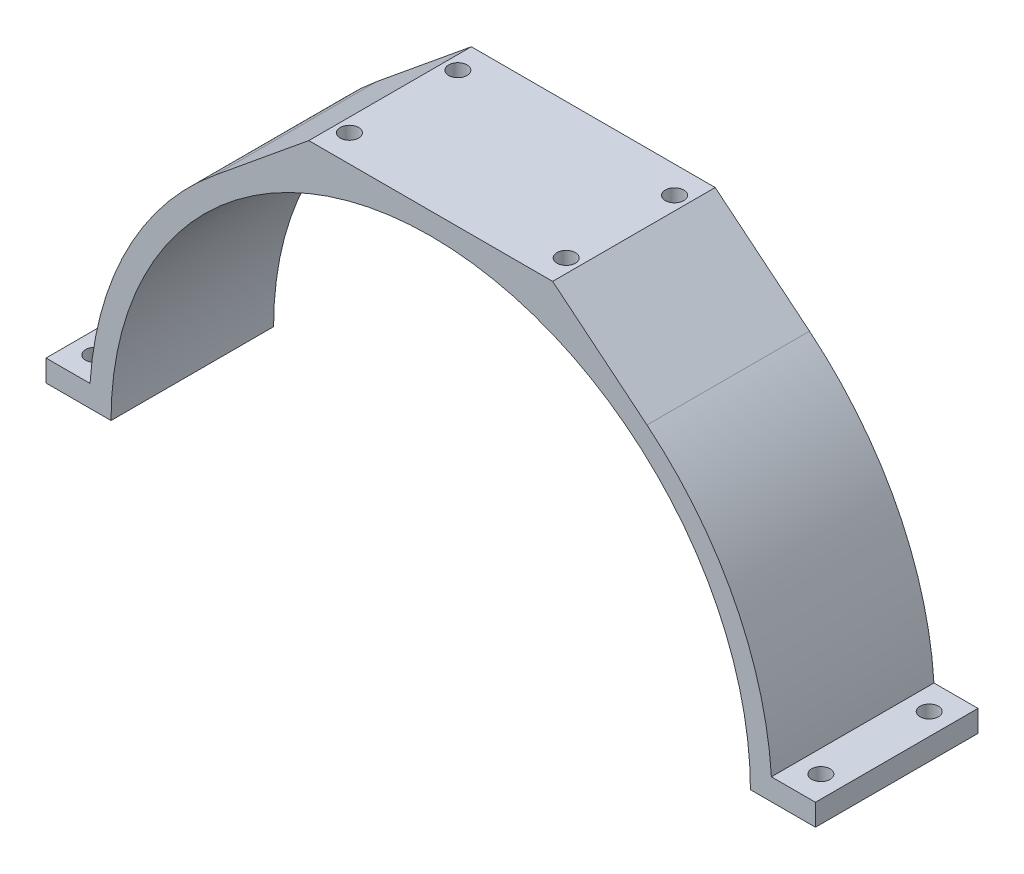
SolidWorks part; units mm, degrees
ref_plane "Plan de face" through (0, 0, 0) normal (0, 0, 1) x (1, 0, 0)
ref_plane "Plan de dessus" through (0, 0, 0) normal (0, 1, 0) x (1, 0, 0)
ref_plane "Plan de droite" through (0, 0, 0) normal (1, 0, 0) x (0, 0, -1)
sketch "Esquisse1" plane through (0, 0, 0) normal (0, 0, 1) x (1, 0, 0)
  line L0 (0, 79.8547) -> (0, -45.4992) construction
  line L1 (22.5, 63) -> (-22.5, 63)
  line L2 (-22.5, 63) -> (-39.9095, 48.7466)
  line L3 (-59, 0) -> (-71, 0)
  line L4 (-71, 0) -> (-71, 4)
  line L5 (-71, 4) -> (-62.8729, 4)
  line L6 (71, 4) -> (62.8729, 4)
  line L7 (71, 0) -> (71, 4)
  line L8 (59, 0) -> (71, 0)
  line L9 (22.5, 63) -> (39.9095, 48.7466)
  arc A0 (-59, 0) -> (59, 0) centre (0, 0) cw
  arc A1 (-62.8729, 4) -> (-39.9095, 48.7466) centre (0, 0) cw
  arc A2 (62.8729, 4) -> (39.9095, 48.7466) centre (0, 0) ccw
  point P25 (0, 63)
  dimension "D1" = 45
  dimension "D4" = 59
  dimension "D5" = 4
  dimension "D2" = 4
  dimension "D3" = 12
  dimension "D6" = 63
extrude "Boss.-Extru.1" add sketch "Esquisse1" along normal blind 30
hole_wizard "Dégagement M31" positions "Esquisse2" profile "Esquisse3" hole size "M3" standard "ISO" end condition through all
sketch "Esquisse2" plane through (0, 4, 0) normal (0, 1, 0) x (1, 0, 0)
  line L0 (-62.8729, 0) -> (-71, 0) construction
  line L1 (-71, -30) -> (-71, 0) construction
  line L2 (-62.8729, -30) -> (-71, -30) construction
  line L3 (71, 0) -> (62.8729, 0) construction
  line L4 (71, -30) -> (71, 0) construction
  line L5 (71, -30) -> (62.8729, -30) construction
  point P0 (-67, -25)
  point P4 (-67, -5)
  point P7 (67, -25)
  point P9 (67, -5)
  dimension "D1" = 5
  dimension "D2" = 4
  dimension "D3" = 4
  dimension "D4" = 5
  dimension "D5" = 5
  dimension "D6" = 4
  dimension "D7" = 4
  dimension "D8" = 5
sketch "Esquisse3" plane through (-67, 4, 25) normal (1, 0, 0) x (0, 0, 1)
  line L0 (0, 0) -> (0, 4)
  line L1 (0, 4) -> (1.7, 4)
  line L2 (1.7, 4) -> (1.7, 0)
  line L5 (1.7, 0) -> (0, 0)
  line L11 (0, -6.35) -> (0, 107.95) construction
  dimension "Diamètre du perçage jusqu'au prochain" = 3.4
  dimension "Profondeur du perçage jusqu'au prochain" = 4
hole_wizard "Dégagement M32" positions "Esquisse4" profile "Esquisse5" hole size "M3" standard "ISO" end condition through all
sketch "Esquisse4" plane through (0, 63, 0) normal (0, 1, 0) x (1, 0, 0)
  line L1 (20, -5) -> (-20, -5) construction
  line L2 (20, -5) -> (20, -25) construction
  line L3 (20, -25) -> (-20, -25) construction
  line L4 (-20, -5) -> (-20, -25) construction
  line L5 (-20, -15) -> (-22.5, -15) construction
  line L7 (-22.5, -30) -> (-22.5, 0) construction
  line L8 (20, -15) -> (22.5, -15) construction
  line L9 (22.5, -30) -> (22.5, 0) construction
  line L11 (0, -5) -> (0, 0) construction
  line L12 (22.5, 0) -> (-22.5, 0) construction
  line L14 (0, -25) -> (0, -30) construction
  line L15 (22.5, -30) -> (-22.5, -30) construction
  point P0 (20, -5)
  point P2 (-20, -5)
  point P4 (-20, -25)
  point P6 (20, -25)
  point P70 (-20, -15)
  point P73 (20, -15)
  dimension "D1" = 40
  dimension "D2" = 20
sketch "Esquisse5" plane through (20, 63, 5) normal (1, 0, 0) x (0, 0, 1)
  line L0 (0, 0) -> (0, 63)
  line L1 (0, 63) -> (1.7, 63)
  line L2 (1.7, 63) -> (1.7, 0)
  line L5 (1.7, 0) -> (0, 0)
  line L11 (0, -6.35) -> (0, 107.95) construction
  dimension "Diamètre du perçage jusqu'au prochain" = 3.4
  dimension "Profondeur du perçage jusqu'au prochain" = 63
